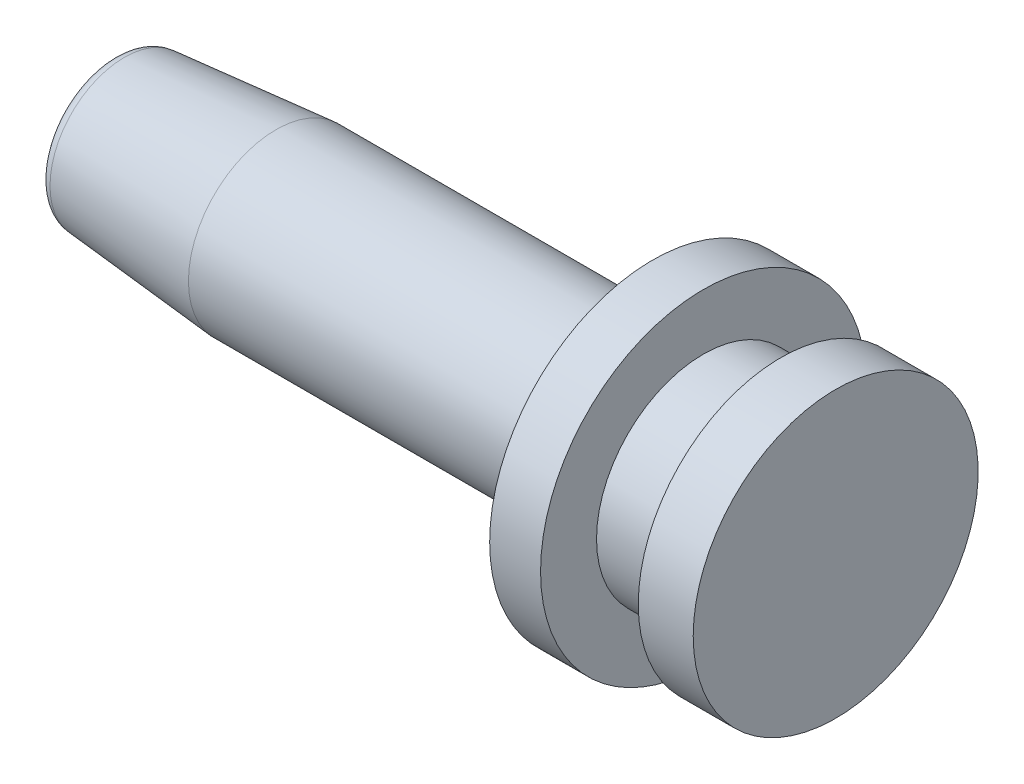
SolidWorks part; units mm, degrees
material "AISI 1020"
ref_plane "Plano superior" through (0, 0, 0) normal (0, 0, 1) x (1, 0, 0)
ref_plane "Plano frontal" through (0, 0, 0) normal (0, 1, 0) x (1, 0, 0)
ref_plane "Plano direito" through (0, 0, 0) normal (1, 0, 0) x (0, 0, -1)
sketch "Esboço1" plane through (0, 0, 0) normal (0, 0, 1) x (1, 0, 0)
  line L0 (0, 0) -> (35.5, 0) construction
  line L1 (35.5, 0) -> (35.5, 7)
  line L2 (35.5, 7) -> (32.8, 7)
  line L3 (32.8, 7) -> (32.8, 5.25)
  line L4 (32.8, 5.25) -> (29, 5.25)
  line L5 (29, 5.25) -> (29, 8)
  line L6 (29, 8) -> (26.5, 8)
  line L7 (26.5, 8) -> (24, 4.3)
  line L8 (24, 4.3) -> (8, 4.3)
  line L9 (8, 4.3) -> (0, 3.6)
  line L10 (0, 3.6) -> (0, 0)
  line L11 (0, 0) -> (35.5, 0)
  dimension "D1" = 35.5
  dimension "D2" = 4.3
  dimension "D3" = 7
  dimension "D4" = 5.25
  dimension "D5" = 8
  dimension "D6" = 3.6
  dimension "D7" = 8
  dimension "D8" = 2.7
  dimension "D9" = 3.8
  dimension "D10" = 2.5
  dimension "D11" = 2.5
revolve "Revolução1" add sketch "Esboço1" angle 360 about L0
fillet "Filete1" radius 0.6 1 edges at (0, 0, 3.6)
